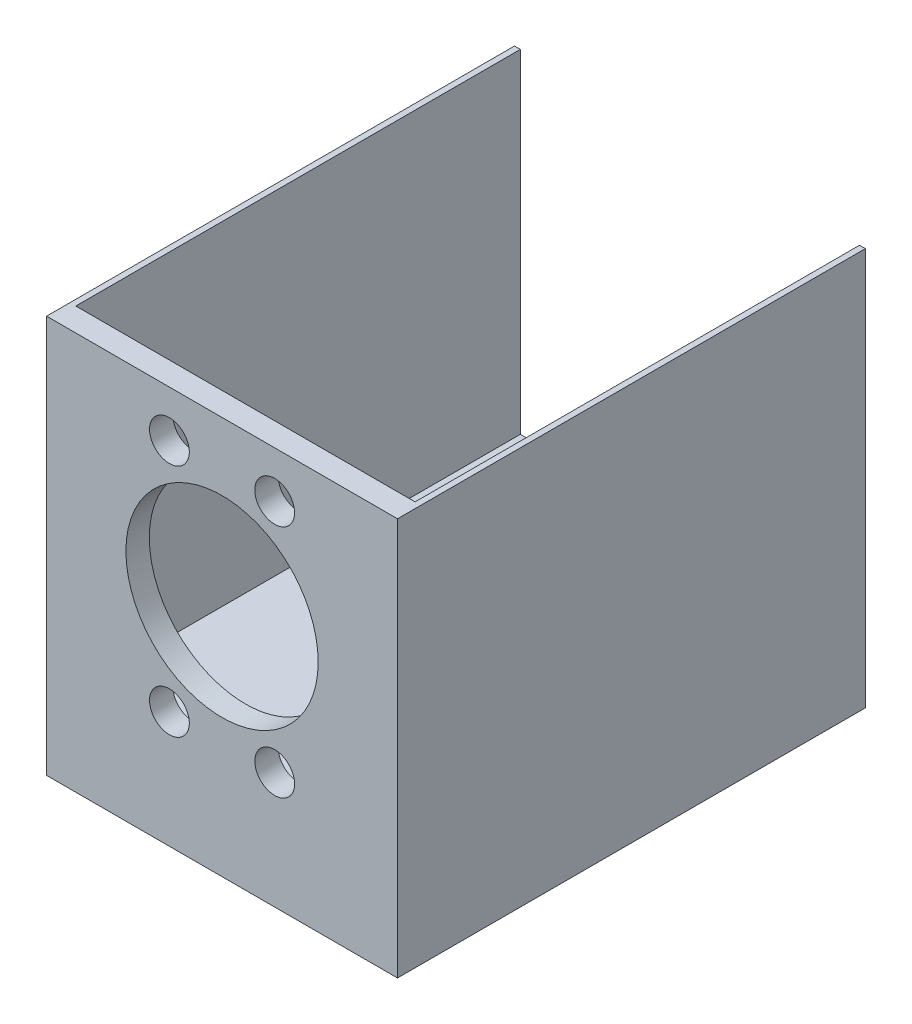
SolidWorks part; units mm, degrees
ref_plane "Front Plane" through (0, 0, 0) normal (0, 0, 1) x (1, 0, 0)
ref_plane "Top Plane" through (0, 0, 0) normal (0, 1, 0) x (1, 0, 0)
ref_plane "Right Plane" through (0, 0, 0) normal (1, 0, 0) x (0, 0, -1)
sketch "Sketch1" plane through (0, 0, 0) normal (0, 0, 1) x (1, 0, 0)
  line L1 (-15, -15) -> (15, -15)
  line L2 (-15, -15) -> (-15, 15)
  line L3 (-15, 15) -> (15, 15)
  line L4 (15, -15) -> (15, 15)
  line L5 (-15, -15) -> (15, 15) construction
  line L6 (-15, 15) -> (15, -15) construction
  point P0 (0, 0)
  dimension "D1" = 30
  dimension "D2" = 30
extrude "Boss-Extrude1" add sketch "Sketch1" against normal blind 40
sketch "Sketch7" plane through (0, 0, -40) normal (0, 0, -1) x (-1, 0, 0)
  line L1 (-14.5, -14.5) -> (14.5, -14.5)
  line L2 (-14.5, -14.5) -> (-14.5, 14.5)
  line L3 (-14.5, 14.5) -> (14.5, 14.5)
  line L4 (14.5, -14.5) -> (14.5, 14.5)
  line L5 (-14.5, -14.5) -> (14.5, 14.5) construction
  line L6 (-14.5, 14.5) -> (14.5, -14.5) construction
  point P0 (0, 0)
  dimension "D1" = 29
  dimension "D2" = 29
extrude "Cut-Extrude5" cut sketch "Sketch7" against normal blind 38
ref_plane "Plane1" through (0, 0, -40) normal (0, 0, 1) x (1, 0, 0)
hole_wizard "CSK for M3 Cross Countersunk Head Screw1" positions "Sketch16" profile "Sketch17" countersink size "M3" standard "AS" end condition through all
sketch "Sketch16" plane through (0, 0, -40) normal (0, 0, 1) x (1, 0, 0)
  line L4 (0, 15) -> (0, -15) construction
  line L5 (15, 15) -> (-15, 15) construction
  line L6 (-15, -15) -> (15, -15) construction
  circle A0 centre (0, 0) radius 11 construction
  point P0 (-4.5, 10.0374)
  point P2 (4.5, 10.0374)
  point P4 (4.5, -10.0374)
  point P6 (-4.5, -10.0374)
  dimension "D2" = 22
  dimension "D1" = 9
  dimension "D4" = 9
sketch "Sketch17" plane through (-4.5, 10.0374, -40) normal (1, 0, 0) x (0, 1, 0)
  line L0 (0, 0) -> (0, 40)
  line L1 (0, 40) -> (1.7, 40)
  line L2 (1.7, 40) -> (1.7, 1.2554)
  line L3 (1.7, 1.2554) -> (3, 0)
  line L5 (3, 0) -> (0, 0)
  line L6 (-1.7, 1.2554) -> (-3, 0) construction
  line L11 (0, -6.35) -> (0, 107.95) construction
  dimension "Thru Hole Dia." = 3.4
  dimension "Thru Hole Depth" = 40
  dimension "Near C'Sink Dia." = 6
  dimension "Near C'Sink Angle" = 92
sketch "Sketch18" plane through (0, 15, 0) normal (0, 1, 0) x (1, 0, 0)
  line L0 (-15.95, 40) -> (15.95, 40) construction
  line L1 (-15, 40) -> (15, 40)
  line L2 (-15, 40) -> (-15, 0)
  line L3 (-15, 0) -> (15, 0)
  line L4 (15, 40) -> (15, 0)
  line L5 (-15, 40) -> (-15, 0) construction
extrude "Cut-Extrude6" cut sketch "Sketch18" against normal blind 1
sketch "Sketch19" plane through (0, -15, 0) normal (0, -1, 0) x (1, 0, 0)
  line L0 (0, 0) -> (0, -40) construction
  line L1 (15.95, -40) -> (-15.95, -40) construction
  line L2 (-15, 0) -> (15, 0) construction
  line L3 (-15, -40) -> (-15, 0) construction
  circle A0 centre (-12, -5) radius 1.55
  circle A1 centre (-12, -37) radius 1.55
  circle A2 centre (12, -37) radius 1.55
  circle A3 centre (12, -5) radius 1.55
  dimension "D1" = 3.1
  dimension "D2" = 3.1
  dimension "D3" = 5
  dimension "D4" = 3
  dimension "D5" = 3
  dimension "D6" = 3
extrude "Cut-Extrude7" cut sketch "Sketch19" against normal blind 1
sketch "Sketch20" plane through (0, 0, 0) normal (0, 0, 1) x (1, 0, 0)
  circle A0 centre (0, 0) radius 8.2178
extrude "Cut-Extrude8" cut sketch "Sketch20" against normal through all both and the other way through all
sketch "Sketch22" plane through (0, -15, 0) normal (0, -1, 0) x (1, 0, 0)
  line L0 (15, -40) -> (14.5, -40)
  line L1 (15, -40) -> (14.5, -40)
  line L2 (14.5, -40) -> (-14.5, -40)
  line L3 (14.5, -40) -> (-14.5, -40)
  line L4 (-14.5, -40) -> (-15, -40)
  line L5 (-14.5, -40) -> (-15, -40)
  line L6 (-15, -40) -> (-15, 0)
  line L7 (-15, -40) -> (-15, 0)
  line L8 (-15, 0) -> (15, 0)
  line L9 (-15, 0) -> (15, 0)
  line L10 (15, 0) -> (15, -40)
  line L11 (15, 0) -> (15, -40)
  circle A0 centre (-12, -5) radius 1.5
  circle A1 centre (12, -5) radius 1.518
  circle A2 centre (-12, -37) radius 1.5
  circle A3 centre (12, -37) radius 1.5
extrude "Boss-Extrude2" add sketch "Sketch22" along normal blind 5
